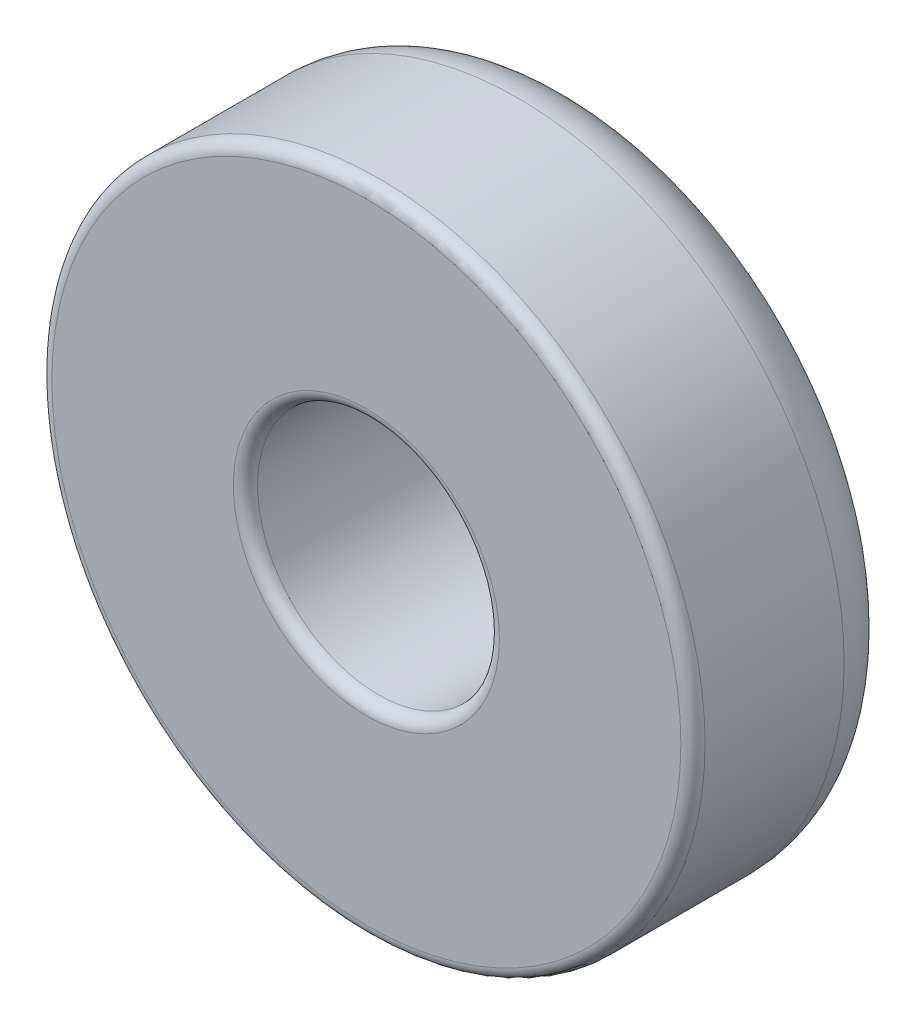
SolidWorks part; units mm, degrees
ref_plane "Front Plane" through (0, 0, 0) normal (0, 0, 1) x (1, 0, 0)
ref_plane "Top Plane" through (0, 0, 0) normal (0, 1, 0) x (1, 0, 0)
ref_plane "Right Plane" through (0, 0, 0) normal (1, 0, 0) x (0, 0, -1)
sketch "Sketch1" plane through (0, 0, 0) normal (0, 0, 1) x (1, 0, 0)
  circle A0 centre (0, 0) radius 1
  dimension "D1" = 2
extrude "Extrude-Thin1" add sketch "Sketch1" along normal blind 1.75 thin
fillet "Fillet1" radius 0.5 1 edges at (2.7, 0, 0)
fillet "Fillet2" radius 0.1 3 edges at (1, 0, 1.75) (2.7, 0, 1.75) (1, 0, 0)
